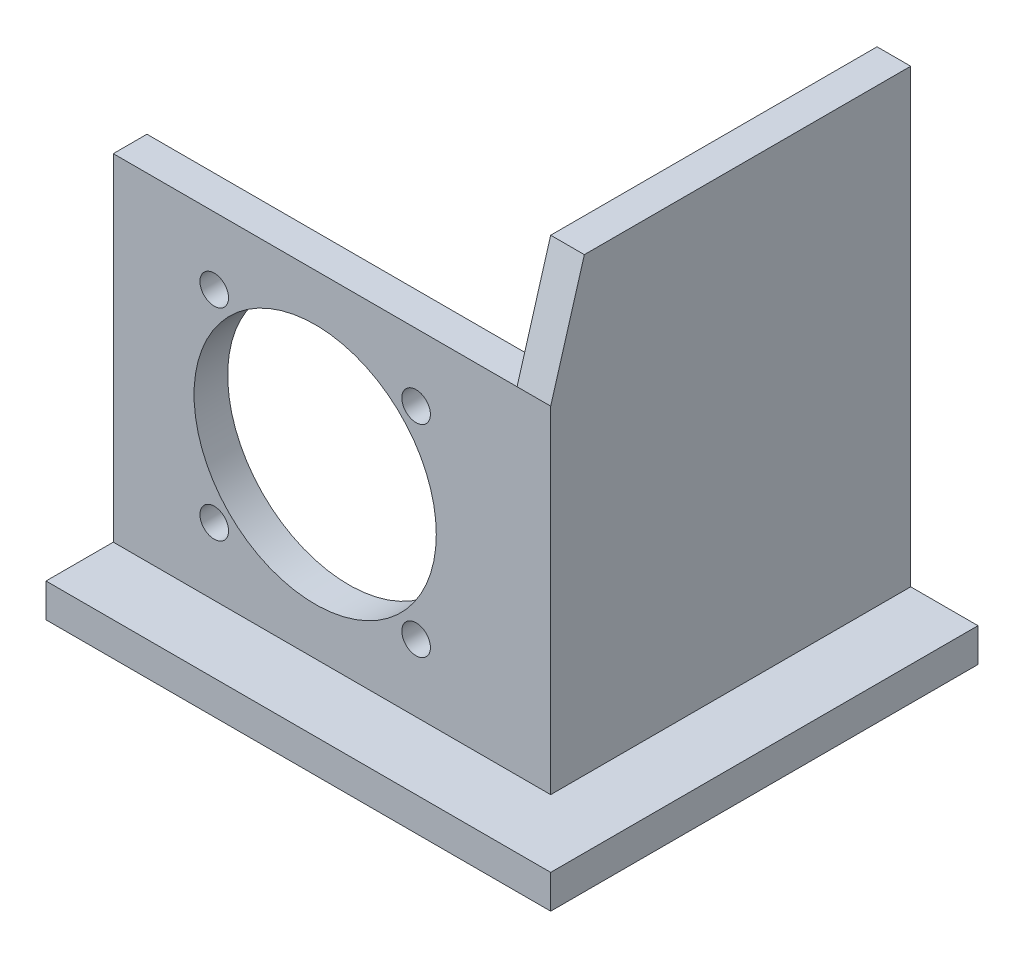
SolidWorks part; units mm, degrees
ref_plane "Front" through (0, 0, 0) normal (0, 0, 1) x (1, 0, 0)
ref_plane "Top" through (0, 0, 0) normal (0, 1, 0) x (1, 0, 0)
ref_plane "Right" through (0, 0, 0) normal (1, 0, 0) x (0, 0, -1)
sketch "Sketch1" plane through (0, 0, 0) normal (0, 0, 1) x (1, 0, 0)
  line L0 (0, 0) -> (0, -60) construction
  line L1 (0, -60) -> (0, -90) construction
  line L2 (0, -30) -> (-30, -30) construction
  line L5 (30, -90) -> (30, 20)
  line L8 (-30, -30) -> (-30, 20) construction
  line L9 (-90, -90) -> (-90, 20)
  line L10 (30, 20) -> (-90, 20)
  line L11 (30, -90) -> (-90, -90)
  circle A0 centre (0, 0) radius 4.25
  circle A1 centre (0, -60) radius 4.25
  circle A3 centre (-30, -30) radius 36
  circle A4 centre (-60, 0) radius 4.25
  circle A5 centre (-60, -60) radius 4.25
  dimension "D2" = 8.5
  dimension "D1" = 60
  dimension "D3" = 30
  dimension "D6" = 30
extrude "Boss-Extrude1" add sketch "Sketch1" along normal blind 10
sketch "Sketch2" plane through (30, 0, 0) normal (1, 0, 0) x (0, 0, -1)
  line L1 (-10, -90) -> (97, -90)
  line L2 (-10, -90) -> (-10, 54)
  line L3 (-10, 54) -> (97, 54)
  line L4 (97, -90) -> (97, 54)
  line L5 (-10, -90) -> (97, 54) construction
  line L6 (-10, 54) -> (97, -90) construction
  point P4 (43.5, -18)
  point P6 (0, 0)
  dimension "D1" = 107
  dimension "D2" = 144
extrude "Boss-Extrude2" add sketch "Sketch2" along normal blind 10
chamfer "Chamfer1" distance 10 distance2 34 1 edges at (35, 54, 10)
sketch "Sketch6" plane through (0, -90, 0) normal (0, -1, 0) x (1, 0, 0)
  line L9 (-90, 30) -> (-90, 10)
  line L10 (-90, 10) -> (40, 10)
  line L11 (60, 30) -> (60, -97)
  line L12 (-90, 30) -> (60, 30)
  line L13 (60, 30) -> (60, -97)
  line L14 (-90, 30) -> (60, 30)
  line L15 (40, 10) -> (40, -97)
  line L16 (40, -97) -> (60, -97)
  dimension "D1" = 20
extrude "Boss-Extrude4" add sketch "Sketch6" against normal blind 10
